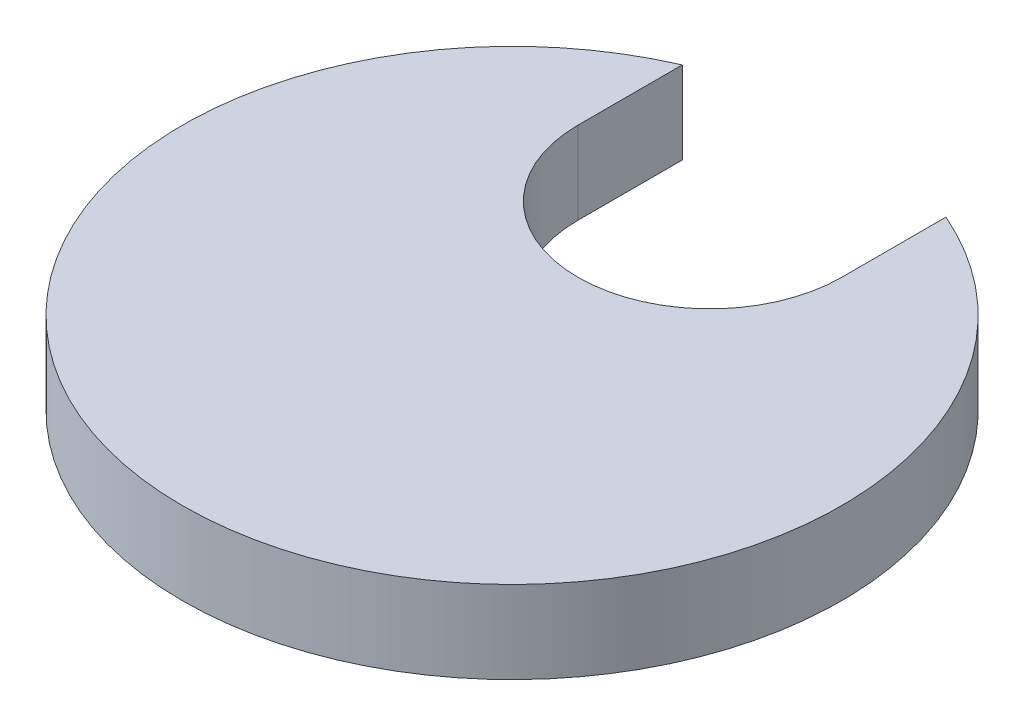
SolidWorks part; units mm, degrees
ref_plane "Front Plane" through (0, 0, 0) normal (0, 0, 1) x (1, 0, 0)
ref_plane "Top Plane" through (0, 0, 0) normal (0, 1, 0) x (1, 0, 0)
ref_plane "Right Plane" through (0, 0, 0) normal (1, 0, 0) x (0, 0, -1)
sketch "Sketch1" plane through (0, 0, 0) normal (0, 1, 0) x (1, 0, 0)
  line L0 (-4, 6) -> (-4, 9.1652)
  line L1 (4, 6) -> (4, 9.1652)
  circle A0 centre (0, 0) radius 10
  circle A1 centre (0, 6) radius 4
  dimension "D1" = 20
  dimension "D2" = 8
  dimension "D3" = 4
extrude "Boss-Extrude1" add sketch "Sketch1" along normal blind 2.5 contours A1 L0 A0 L1
